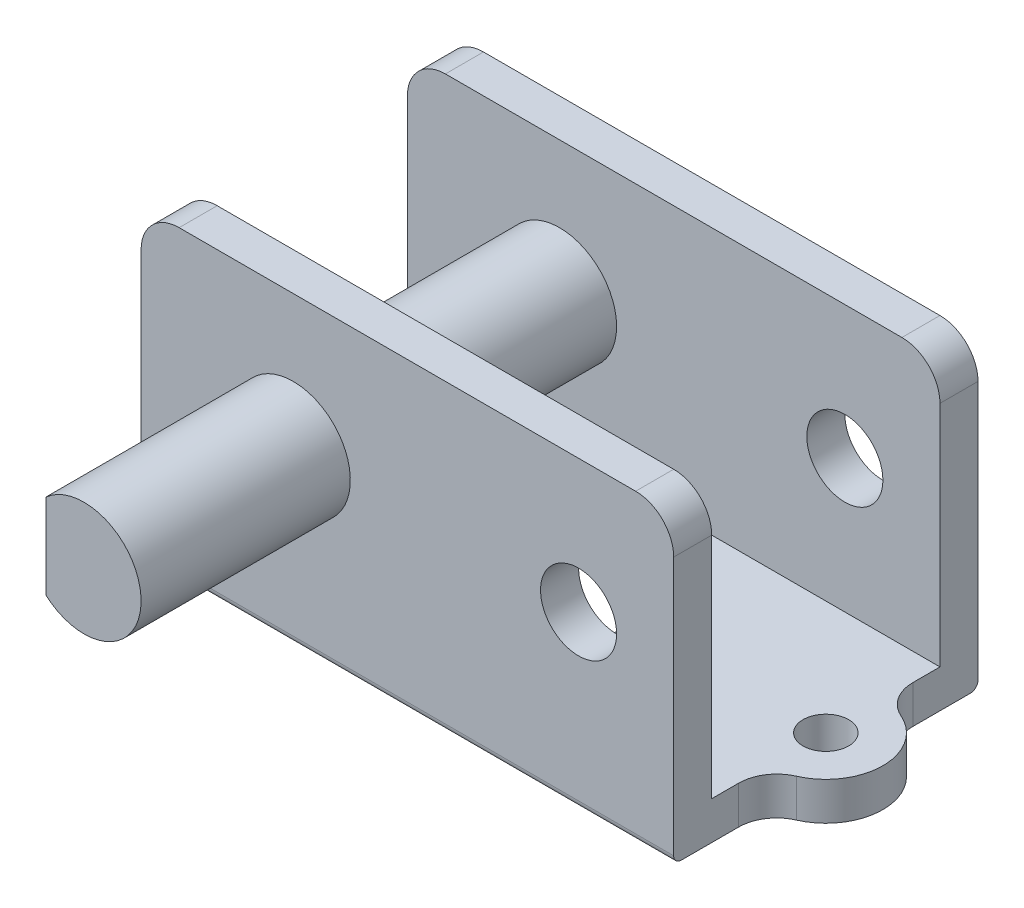
SolidWorks part; units mm, degrees
ref_plane "Спереди" through (0, 0, 0) normal (0, 0, 1) x (1, 0, 0)
ref_plane "Сверху" through (0, 0, 0) normal (0, 1, 0) x (1, 0, 0)
ref_plane "Справа" through (0, 0, 0) normal (1, 0, 0) x (0, 0, -1)
sketch "Sketch1" plane through (0, 0, 0) normal (0, 0, 1) x (1, 0, 0)
  line L0 (0, 0) -> (-7, 0)
  line L1 (-7, 0) -> (-7, 8)
  line L2 (-7, 8) -> (7, 8)
  line L3 (7, 8) -> (7, 0)
  line L4 (7, 0) -> (0, 0)
extrude "Extrude1" add sketch "Sketch1" along normal mid plane 8
sketch "Sketch2" plane through (0, 0, 0) normal (0, 0, 1) x (1, 0, 0)
  line L0 (7, 8) -> (7, 4.5) construction
  line L1 (7, 4.5) -> (4.5, 4.5) construction
  circle A0 centre (4.5, 4.5) radius 1
extrude "Extrude2" cut sketch "Sketch2" against normal through all both and the other way through all
sketch "Sketch3" plane through (0, 0, 0) normal (0, 0, 1) x (1, 0, 0)
  line L0 (-7, 8) -> (-3, 8)
  line L1 (-3, 8) -> (-3, 4.5)
  circle A0 centre (-3, 4.5) radius 1.5
sketch "Sketch4" plane through (0, 0, 0) normal (1, 0, 0) x (0, 0, -1)
  line L0 (0, 0) -> (0, 1)
  line L1 (3, 1) -> (-3, 1)
  line L2 (-3, 1) -> (-3, 9.732)
  line L3 (3, 1) -> (3, 9.732)
  line L4 (-3, 9.732) -> (3, 9.732)
extrude "Extrude3" cut sketch "Sketch4" against normal through all both and the other way through all contours L4 L2 L1 L3
fillet "Fillet1" radius 0.2 2 edges at (0, 0, 4) (0, 0, -4)
fillet "Fillet2" radius 1 4 edges at (7, 8, -3.5) (7, 8, 3.5) (-7, 8, -3.5) (-7, 8, 3.5)
extrude "Extrude4" add sketch "Sketch3" along normal blind 14 and the other way blind 3
sketch "Sketch5" plane through (0, 0, 14) normal (0, 0, 1) x (1, 0, 0)
  line L0 (-1.5, 4.5) -> (-4, 4.5)
  line L1 (-4, 4.5) -> (-4, 6.0607)
  line L2 (-4, 6.0607) -> (-4.9564, 6.0607)
  line L3 (-4.9564, 6.0607) -> (-4.9564, 2.5)
  line L4 (-4.9564, 2.5) -> (-4, 2.5)
  line L5 (-4, 2.5) -> (-4, 4.5)
  circle A0 centre (-3, 4.5) radius 1.5 construction
  circle A1 centre (-3, 4.5) radius 1.5 construction
  circle M1 centre (-3, 4.5) radius 1.5
extrude "Extrude5" cut sketch "Sketch5" against normal blind 9 contours L4 L5 L1 L2 L3 M1 | L5 L1 M1
sketch "Sketch6" plane through (0, 0, 0) normal (0, -1, 0) x (1, 0, 0)
  line L0 (0, 0) -> (-8.5, 0)
  line L2 (0, 0) -> (0, 5.5899)
  circle A1 centre (-7, 0) radius 1.5
  circle A2 centre (0, 0) radius 6
  circle A3 centre (7, 0) radius 1.5
extrude "Extrude6" add sketch "Sketch6" against normal blind 1
sketch "Sketch7" plane through (0, 0, 0) normal (0, -1, 0) x (1, 0, 0)
  circle A0 centre (-7, 0) radius 0.6
  circle A1 centre (7, 0) radius 0.6
extrude "Extrude7" cut sketch "Sketch7" against normal blind 1
fillet "Fillet3" radius 1 4 edges at (7, 0.5, -1.5) (7, 0.5, 1.5) (-7, 0.5, 1.5) (-7, 0.5, -1.5)
sketch "Sketch8" plane through (0, 0, 0) normal (0, -1, 0) x (1, 0, 0)
  circle A0 centre (0, 0) radius 2
extrude "Extrude8" cut sketch "Sketch8" against normal blind 1
sketch "Sketch9" plane through (0, 0, 0) normal (1, 0, 0) x (0, 0, -1)
  line L0 (-4, 4.5) -> (-9.5, 4.5)
  line L1 (-4, 6) -> (-4, 3) construction
  line L2 (-9.5, 4.5) -> (-9.5, 7.3176)
  line L3 (-9.5, 7.3176) -> (-15.4224, 7.3176)
  line L4 (-15.4224, 7.3176) -> (-15.4224, 4.5)
  line L5 (-15.4224, 4.5) -> (-9.5, 4.5)
  line L6 (-15.4224, 4.5) -> (-15.4224, 0.3826)
  line L7 (-15.4224, 0.3826) -> (-9.5, 0.3826)
  line L8 (-9.5, 0.3826) -> (-9.5, 4.5)
  dimension "D1" = 5.5
extrude "Extrude9" cut sketch "Sketch9" against normal through all contours L4 L5 L2 L3 | L7 L8 L5 L6
